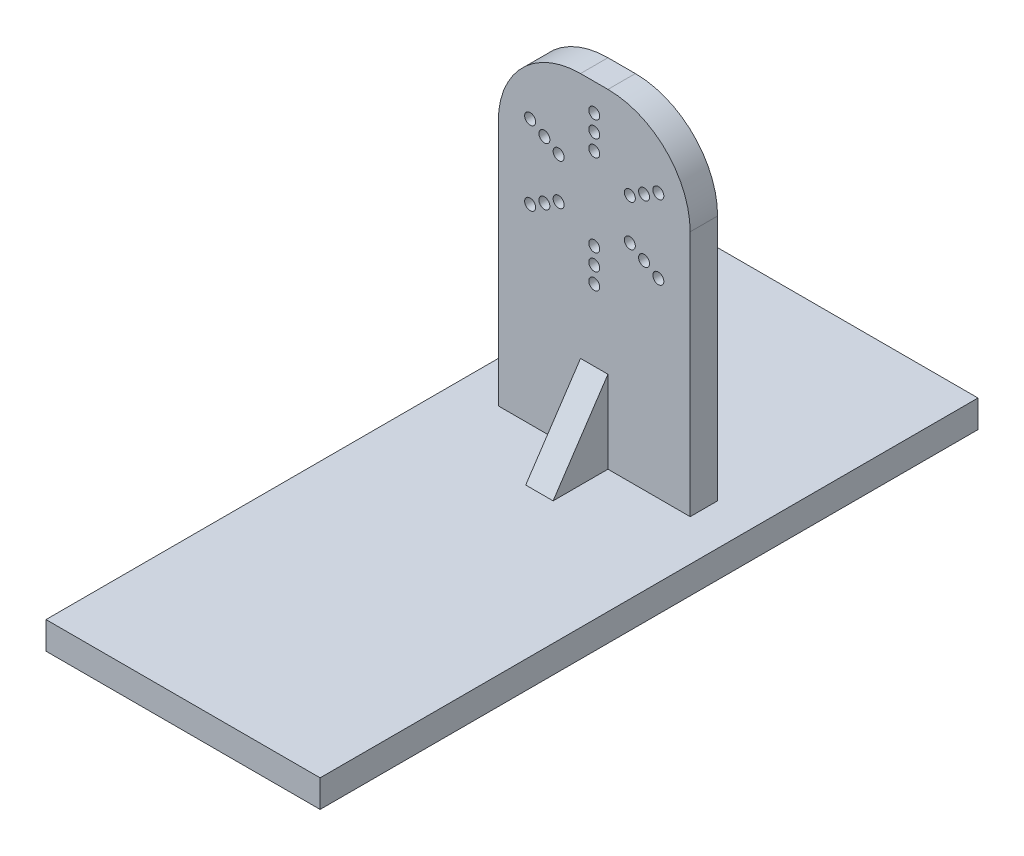
SolidWorks part; units mm, degrees
material "Polylactic Acid"
ref_plane "Front Plane" through (0, 0, 0) normal (0, 0, 1) x (1, 0, 0)
ref_plane "Top Plane" through (0, 0, 0) normal (0, 1, 0) x (1, 0, 0)
ref_plane "Right Plane" through (0, 0, 0) normal (1, 0, 0) x (0, 0, -1)
sketch "Sketch1" plane through (0, 0, 0) normal (0, 0, 1) x (1, 0, 0)
  line L1 (-17.5, -30) -> (17.5, -30)
  line L2 (-17.5, -30) -> (-17.5, 30)
  line L3 (-17.5, 30) -> (17.5, 30)
  line L4 (17.5, -30) -> (17.5, 30)
  line L5 (-17.5, -30) -> (17.5, 30) construction
  line L6 (-17.5, 30) -> (17.5, -30) construction
  point P0 (0, 0)
  dimension "D1" = 35
  dimension "D2" = 60
extrude "Boss-Extrude1" add sketch "Sketch1" along normal mid plane 5
sketch "Sketch2" plane through (0, 0, -2.5) normal (0, 0, -1) x (-1, 0, 0)
  line L0 (0, 25) -> (0, 22) construction
  line L1 (0, 11.5) -> (0, 19) construction
  line L2 (-17.5, 30) -> (17.5, 30) construction
  circle A0 centre (0, 25) radius 1
  circle A3 centre (0, 22) radius 1
  circle A4 centre (0, 19) radius 1
  circle A5 centre (11.6913, 18.25) radius 1
  circle A6 centre (9.0933, 16.75) radius 1
  circle A7 centre (6.4952, 15.25) radius 1
  circle A8 centre (11.6913, 4.75) radius 1
  circle A9 centre (9.0933, 6.25) radius 1
  circle A10 centre (6.4952, 7.75) radius 1
  circle A11 centre (0, -2) radius 1
  circle A12 centre (0, 1) radius 1
  circle A13 centre (0, 4) radius 1
  circle A14 centre (-11.6913, 4.75) radius 1
  circle A15 centre (-9.0933, 6.25) radius 1
  circle A16 centre (-6.4952, 7.75) radius 1
  circle A17 centre (-11.6913, 18.25) radius 1
  circle A18 centre (-9.0933, 16.75) radius 1
  circle A19 centre (-6.4952, 15.25) radius 1
  dimension "D1" = 2
  dimension "D3" = 3
  dimension "D5" = 7.5
  dimension "D6" = 5
  dimension "D2" = 3
  dimension "D4" = 6
extrude "Cut-Extrude1" cut sketch "Sketch2" against normal up to surface (5 mm away) up to face at (0, 0, 2.5)
fillet "Fillet1" radius 15 2 edges at (17.5, 30, 0) (-17.5, 30, 0)
sketch "Sketch3" plane through (0, 0, -2.5) normal (0, 0, -1) x (-1, 0, 0)
  line L0 (17.5, -30) -> (-17.5, -30) construction
  line L1 (-25, -35) -> (25, -35)
  line L2 (-25, -35) -> (-25, -30)
  line L3 (-25, -30) -> (25, -30)
  line L4 (25, -35) -> (25, -30)
  point P6 (0, -30)
  dimension "D1" = 50
  dimension "D2" = 5
extrude "Boss-Extrude2" add sketch "Sketch3" against normal blind 80
sketch "Sketch4" plane through (0, 0, 0) normal (1, 0, 0) x (0, 0, -1)
  line L0 (-12.5, -30) -> (-2.5, -30)
  line L1 (-77.5, -30) -> (2.5, -30) construction
  line L2 (-2.5, -30) -> (-2.5, -15)
  line L4 (-2.5, -15) -> (-12.5, -30)
  line L5 (-77.5, -30) -> (2.5, -30) construction
  line L6 (-2.5, -30) -> (-2.5, 15) construction
  line L7 (-2.5, -30) -> (2.5, -30) construction
  dimension "D1" = 10
  dimension "D2" = 15
extrude "Boss-Extrude3" add sketch "Sketch4" along normal mid plane 5
sketch "Sketch5" plane through (0, 0, -2.5) normal (0, 0, -1) x (-1, 0, 0)
  line L1 (-25, -30) -> (25, -30)
  line L2 (-25, -30) -> (-25, -35)
  line L3 (-25, -35) -> (25, -35)
  line L4 (25, -30) -> (25, -35)
extrude "Boss-Extrude4" add sketch "Sketch5" along normal blind 40
sketch "Sketch6" plane through (0, 0, 0) normal (1, 0, 0) x (0, 0, -1)
  line L0 (2.5, -30) -> (8.5, -30)
  line L1 (-77.5, -30) -> (42.5, -30) construction
  line L2 (8.5, -30) -> (2.5, -20)
  line L3 (2.5, -30) -> (2.5, 15) construction
  line L4 (2.5, -20) -> (2.5, -30)
  dimension "D1" = 10
  dimension "D2" = 6
extrude "Boss-Extrude5" add sketch "Sketch6" along normal mid plane 3
